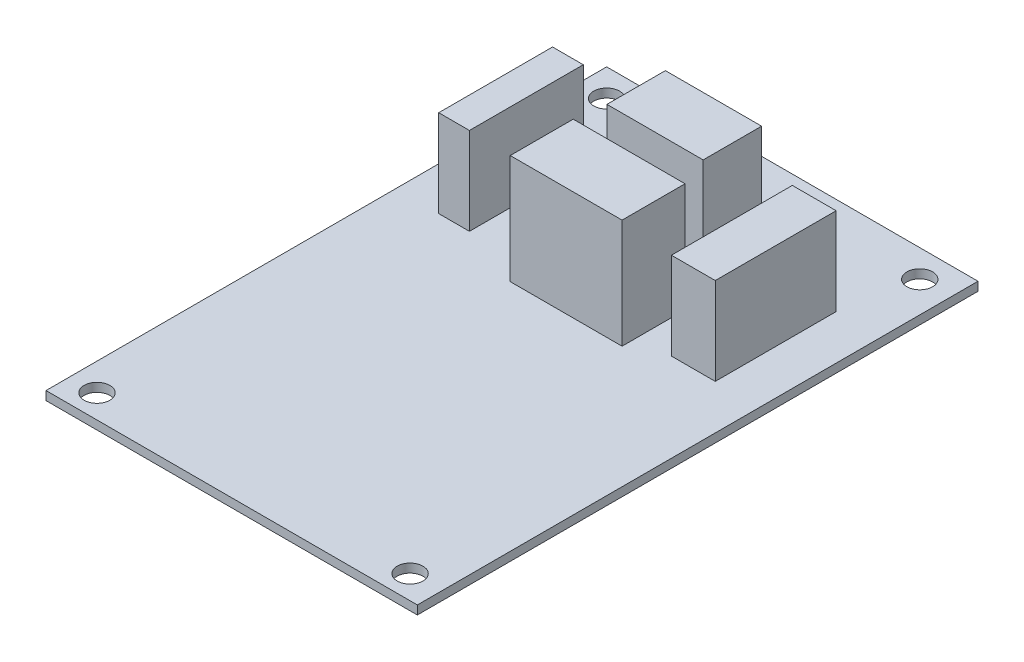
SolidWorks part; units mm, degrees
ref_plane "Front Plane" through (0, 0, 0) normal (0, 0, 1) x (1, 0, 0)
ref_plane "Top Plane" through (0, 0, 0) normal (0, 1, 0) x (1, 0, 0)
ref_plane "Right Plane" through (0, 0, 0) normal (1, 0, 0) x (0, 0, -1)
sketch "Sketch1" plane through (0, 0, 0) normal (0, 1, 0) x (1, 0, 0)
  line L1 (0, 0) -> (51, 0)
  line L2 (0, 0) -> (0, -77)
  line L3 (0, -77) -> (51, -77)
  line L4 (51, 0) -> (51, -77)
  dimension "D1" = 51
  dimension "D2" = 77
extrude "Boss-Extrude1" add sketch "Sketch1" along normal blind 1.2
sketch "Sketch2" plane through (0, 1.2, 0) normal (0, 1, 0) x (1, 0, 0)
  line L0 (51, 0) -> (0, 0) construction
  line L1 (0, 0) -> (0, -77) construction
  circle A0 centre (3.77, -3.77) radius 1.77
  circle A1 centre (46.77, -3.77) radius 1.77
  circle A2 centre (46.77, -73.77) radius 1.77
  circle A3 centre (3.77, -73.77) radius 1.77
  dimension "D1" = 3.54
  dimension "D4" = 3.77
  dimension "D5" = 3.77
  dimension "D2" = 2
  dimension "D3" = 2
extrude "Cut-Extrude1" cut sketch "Sketch2" against normal blind 1.2
sketch "Sketch3" plane through (0, 1.2, 0) normal (0, 1, 0) x (1, 0, 0)
  line L1 (19.4813, -11.4156) -> (32.6948, -11.4156)
  line L2 (19.4813, -11.4156) -> (19.4813, -19.4406)
  line L3 (19.4813, -19.4406) -> (32.6948, -19.4406)
  line L4 (32.6948, -11.4156) -> (32.6948, -19.4406)
  line L5 (18.9278, -23.5223) -> (34.286, -23.5223)
  line L6 (18.9278, -23.5223) -> (18.9278, -32.1699)
  line L7 (18.9278, -32.1699) -> (34.286, -32.1699)
  line L8 (34.286, -23.5223) -> (34.286, -32.1699)
extrude "Boss-Extrude2" add sketch "Sketch3" along normal blind 15
sketch "Sketch4" plane through (0, 1.2, 0) normal (0, 1, 0) x (1, 0, 0)
  line L1 (5.9218, -13.3527) -> (10.1418, -13.3527)
  line L2 (5.9218, -13.3527) -> (5.9218, -28.9876)
  line L3 (5.9218, -28.9876) -> (10.1418, -28.9876)
  line L4 (10.1418, -13.3527) -> (10.1418, -28.9876)
  line L5 (38.8519, -13.3527) -> (44.8707, -13.3527)
  line L6 (38.8519, -13.3527) -> (38.8519, -29.9561)
  line L7 (38.8519, -29.9561) -> (44.8707, -29.9561)
  line L8 (44.8707, -13.3527) -> (44.8707, -29.9561)
extrude "Boss-Extrude3" add sketch "Sketch4" along normal blind 12
equation "\"D4@Sketch2\"=2+3.54/2"
equation "\"D5@Sketch2\"=\"D4@Sketch2\""
